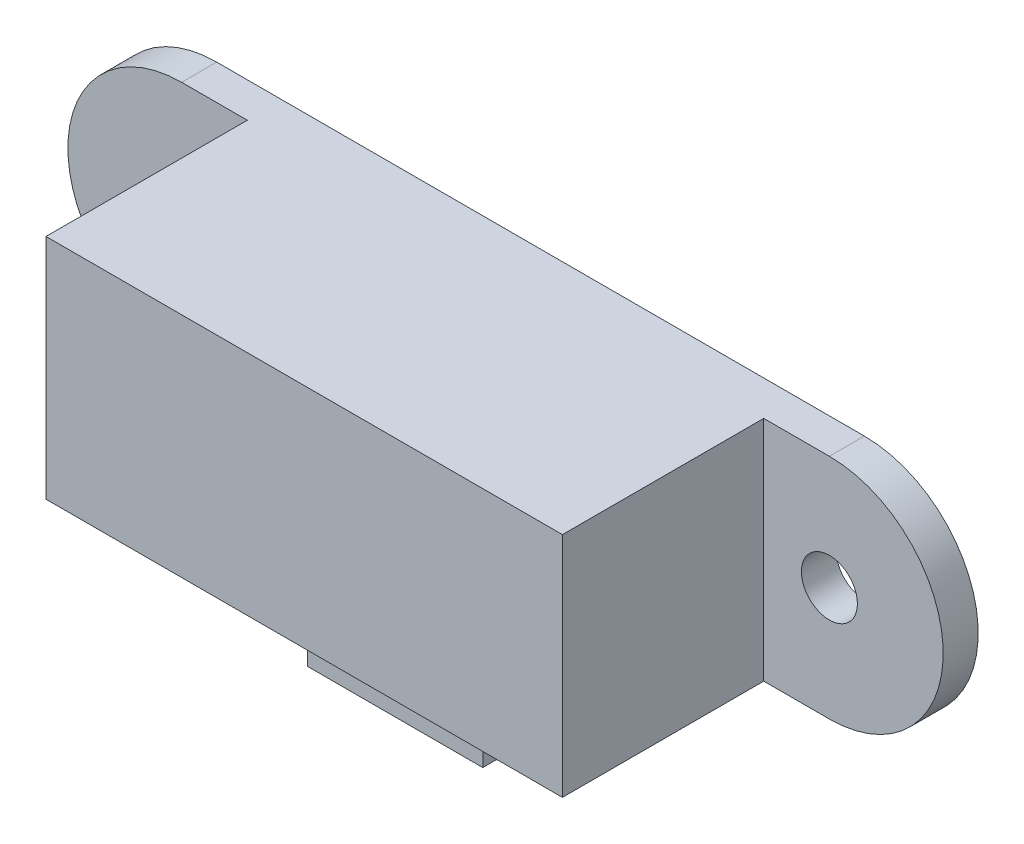
SolidWorks part; units mm, degrees
material "ABS"
ref_plane "Plan de face" through (0, 0, 0) normal (0, 0, 1) x (1, 0, 0)
ref_plane "Plan de dessus" through (0, 0, 0) normal (0, 1, 0) x (1, 0, 0)
ref_plane "Plan de droite" through (0, 0, 0) normal (1, 0, 0) x (0, 0, -1)
sketch "Esquisse1" plane through (0, 0, 0) normal (0, 0, 1) x (1, 0, 0)
  line L0 (-18.5, -6.5) -> (18.5, -6.5)
  line L1 (18.5, 6.5) -> (-18.5, 6.5)
  line L2 (-18.5, 0) -> (18.5, 0) construction
  arc A0 (-18.5, 6.5) -> (-18.5, -6.5) centre (-18.5, 0) ccw
  arc A1 (18.5, 6.5) -> (18.5, -6.5) centre (18.5, 0) cw
  circle A2 centre (-18.5, 0) radius 1.6
  circle A3 centre (18.5, 0) radius 1.6
  dimension "D3" = 3.2
  dimension "D1" = 13
  dimension "D2" = 37
extrude "Extrusion1" add sketch "Esquisse1" along normal blind 2
sketch "Esquisse2" plane through (0, 0, 2) normal (0, 0, 1) x (1, 0, 0)
  line L0 (18.5, 6.5) -> (-18.5, 6.5) construction
  line L1 (-14.75, 6.5) -> (14.75, 6.5)
  line L2 (-14.75, 6.5) -> (-14.75, -6.5)
  line L3 (-14.75, -6.5) -> (14.75, -6.5)
  line L4 (14.75, 6.5) -> (14.75, -6.5)
  line L5 (-18.5, -6.5) -> (18.5, -6.5) construction
  line L6 (0, 6.5) -> (0, -6.5) construction
  dimension "D1" = 29.5
extrude "Extrusion2" add sketch "Esquisse2" along normal blind 11.5
sketch "Esquisse3" plane through (0, -6.5, 0) normal (0, -1, 0) x (1, 0, 0)
  line L0 (0, 0) -> (0, 8.3) construction
  line L1 (-5, 8.3) -> (5, 8.3)
  line L2 (-5, 8.3) -> (-5, 3.3)
  line L3 (-5, 3.3) -> (5, 3.3)
  line L4 (5, 8.3) -> (5, 3.3)
  line L5 (-18.5, 0) -> (18.5, 0) construction
  dimension "D1" = 10
  dimension "D2" = 5
  dimension "D3" = 3.3
extrude "Extrusion3" add sketch "Esquisse3" along normal blind 6
